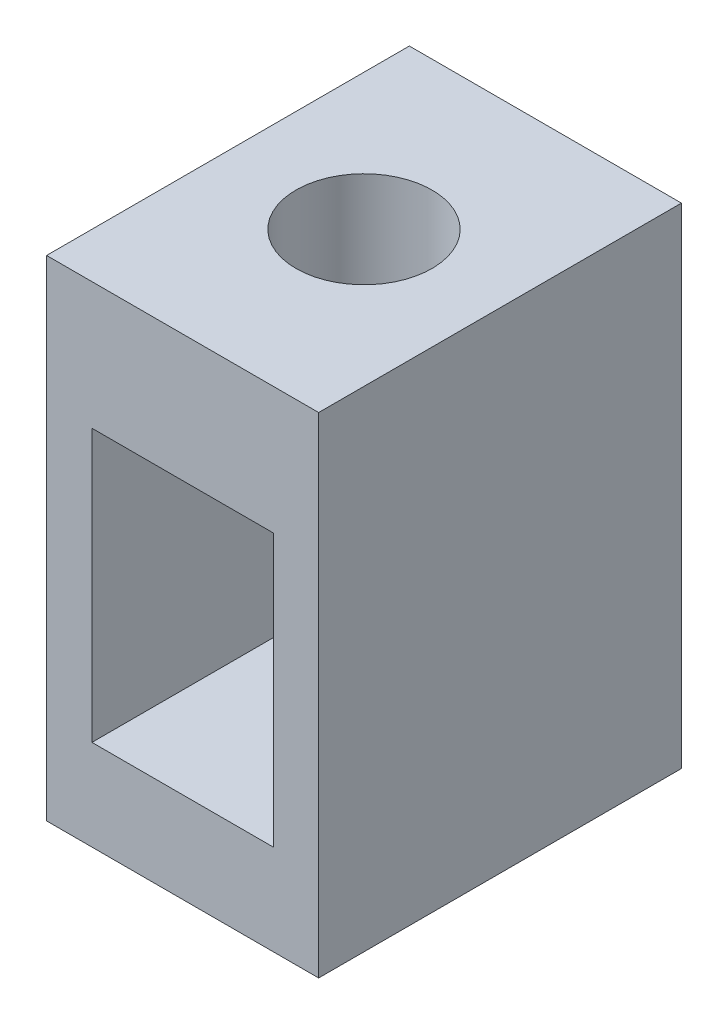
SolidWorks part; units mm, degrees
ref_plane "Спереди" through (0, 0, 0) normal (0, 0, 1) x (1, 0, 0)
ref_plane "Сверху" through (0, 0, 0) normal (0, 1, 0) x (1, 0, 0)
ref_plane "Справа" through (0, 0, 0) normal (1, 0, 0) x (0, 0, -1)
sketch "Эскиз1" plane through (0, 0, 0) normal (0, 0, 1) x (1, 0, 0)
  line L1 (-1.5, 2.7) -> (1.5, 2.7)
  line L2 (-1.5, 2.7) -> (-1.5, -2.7)
  line L3 (-1.5, -2.7) -> (1.5, -2.7)
  line L4 (1.5, 2.7) -> (1.5, -2.7)
  line L5 (-1.5, 2.7) -> (1.5, -2.7) construction
  line L6 (-1.5, -2.7) -> (1.5, 2.7) construction
  point P0 (0, 0)
  dimension "D1" = 3
  dimension "D2" = 5.4
extrude "Бобышка-Вытянуть1" add sketch "Эскиз1" against normal blind 4
sketch "Эскиз2" plane through (0, 0, 0) normal (0, 0, 1) x (1, 0, 0)
  line L0 (-1.5, -2.7) -> (1.5, -2.7) construction
  line L1 (-1, 1.3) -> (1, 1.3)
  line L2 (-1, 1.3) -> (-1, -1.7)
  line L3 (-1, -1.7) -> (1, -1.7)
  line L4 (1, 1.3) -> (1, -1.7)
  line L5 (-1, 1.3) -> (1, -1.7) construction
  line L6 (0, 2.7) -> (0, -2.7) construction
  line L7 (1.5, 2.7) -> (-1.5, 2.7) construction
  point P10 (0, -0.2)
  dimension "D1" = 3
  dimension "D2" = 1
  dimension "D3" = 2
extrude "Вырез-Вытянуть1" cut sketch "Эскиз2" against normal through all
sketch "Эскиз3" plane through (0, 2.7, 0) normal (0, 1, 0) x (1, 0, 0)
  line L0 (-1.5, 4) -> (1.5, 0) construction
  circle A0 centre (0, 2) radius 0.75
  dimension "D1" = 1.5
extrude "Вырез-Вытянуть2" cut sketch "Эскиз3" against normal up to next
